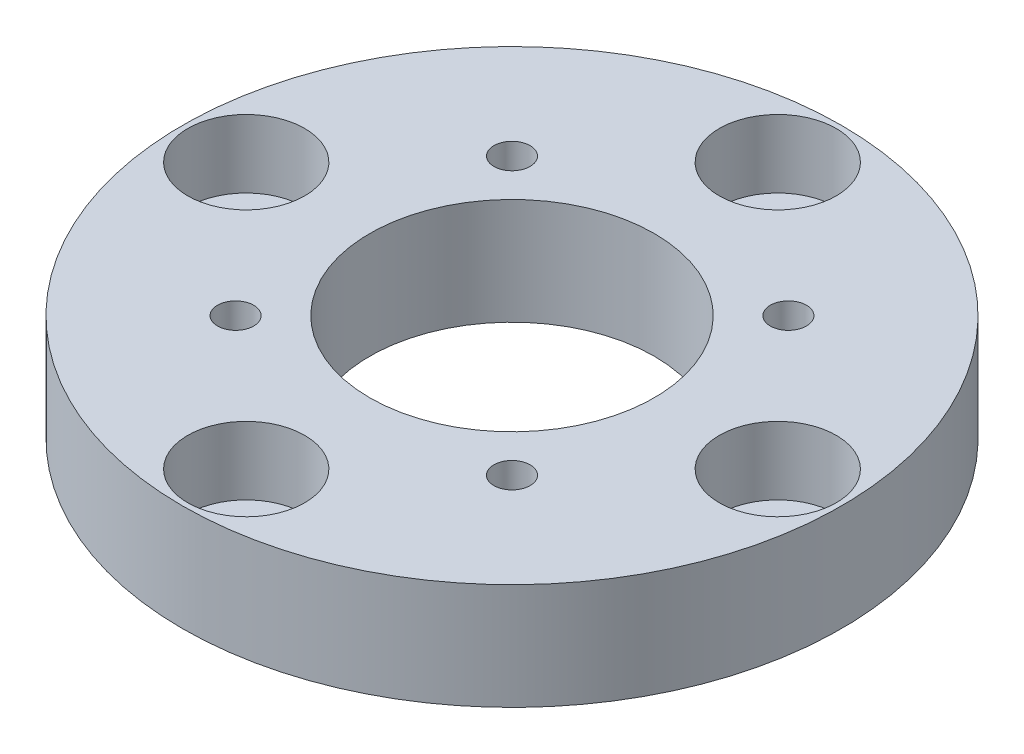
SolidWorks part; units mm, degrees
material "ABS"
ref_plane "Front Plane" through (0, 0, 0) normal (0, 0, 1) x (1, 0, 0)
ref_plane "Top Plane" through (0, 0, 0) normal (0, 1, 0) x (1, 0, 0)
ref_plane "Right Plane" through (0, 0, 0) normal (1, 0, 0) x (0, 0, -1)
sketch "Sketch1" plane through (0, 0, 0) normal (0, 1, 0) x (1, 0, 0)
  line L1 (-13, 13) -> (13, 13) construction
  line L2 (-13, 13) -> (-13, -13) construction
  line L3 (-13, -13) -> (13, -13) construction
  line L4 (13, 13) -> (13, -13) construction
  line L5 (-13, 13) -> (13, -13) construction
  line L6 (-13, -13) -> (13, 13) construction
  circle A0 centre (0, 0) radius 25 construction
  circle A1 centre (0, 0) radius 31
  circle A3 centre (0, 0) radius 18.3848 construction
  circle A4 centre (0, 0) radius 13.3848
  point P12 (10.0192, 8.2835)
  dimension "D1" = 50
  dimension "D4" = 26
  dimension "D2" = 6
  dimension "D3" = 5
extrude "Boss-Extrude1" add sketch "Sketch1" along normal blind 10
hole_wizard "CBORE for M6 Hex Socket Head Cap Screw1" positions "Sketch2" profile "Sketch4" counterbore size "M6" standard "ISO" end condition up to next
sketch "Sketch2" plane through (0, 10, 0) normal (0, 1, 0) x (1, 0, 0)
  circle A1 centre (0, 0) radius 25 construction
  point P4 (0, 25)
sketch "Sketch4" plane through (0, 10, -25) normal (1, 0, 0) x (0, 0, 1)
  line L0 (0, 0) -> (0, 10)
  line L1 (0, 10) -> (3.3, 10)
  line L3 (3.3, 10) -> (3.3, 6.4)
  line L4 (3.3, 6.4) -> (5.5, 6.4)
  line L5 (5.5, 6.4) -> (5.5, 0)
  line L7 (5.5, 0) -> (0, 0)
  line L11 (0, -6.35) -> (0, 107.95) construction
  dimension "Thru Hole Dia." = 6.6
  dimension "Thru Hole Depth" = 10
  dimension "C'Bore Dia." = 11
  dimension "C'Bore Depth" = 6.4
hole_wizard "M3 Clearance Hole1" positions "Sketch5" profile "Sketch7" hole size "M3" standard "ISO" end condition up to next
sketch "Sketch5" plane through (0, 10, 0) normal (0, 1, 0) x (1, 0, 0)
  line L0 (0, 0) -> (-13, 13) construction
  line L2 (0, 0) -> (0, 17.314) construction
  circle A0 centre (0, 0) radius 18.3848 construction
  point P0 (-13, 13)
  dimension "D1" = 45
sketch "Sketch7" plane through (-13, 10, -13) normal (1, 0, 0) x (0, 0, 1)
  line L0 (0, 0) -> (0, 10)
  line L1 (0, 10) -> (1.7, 10)
  line L2 (1.7, 10) -> (1.7, 0)
  line L5 (1.7, 0) -> (0, 0)
  line L11 (0, -6.35) -> (0, 107.95) construction
  dimension "Thru Hole Dia." = 3.4
  dimension "Thru Hole Depth" = 10
pattern_circular "CirPattern1" count 4 over 360 about axis through (0, 0, 0) along (0, 1, 0) of "CBORE for M6 Hex Socket Head Cap Screw1", "M3 Clearance Hole1"
